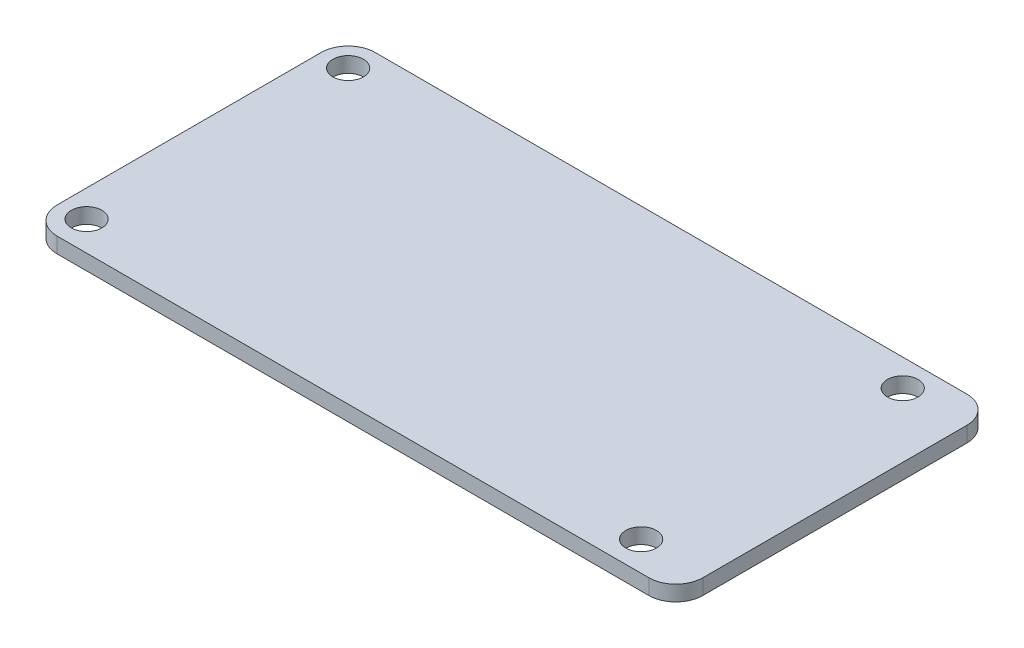
SolidWorks part; units mm, degrees
ref_plane "Front Plane" through (0, 0, 0) normal (0, 0, 1) x (1, 0, 0)
ref_plane "Top Plane" through (0, 0, 0) normal (0, 1, 0) x (1, 0, 0)
ref_plane "Right Plane" through (0, 0, 0) normal (1, 0, 0) x (0, 0, -1)
sketch "Sketch1" plane through (0, 0, 0) normal (0, 1, 0) x (1, 0, 0)
  line L0 (0, 0) -> (0, 27.9326) construction
  line L1 (-33.5, 13.697) -> (-33.5, -13.697)
  line L2 (-30.697, 16.5) -> (30.697, 16.5)
  line L3 (33.5, 13.697) -> (33.5, -13.697)
  line L4 (-30.697, -16.5) -> (30.697, -16.5)
  line L5 (0, 0) -> (-51.5102, 0) construction
  line L6 (-30.697, 13.697) -> (26.843, 13.697) construction
  line L7 (-30.697, 13.697) -> (-30.697, -13.443) construction
  line L8 (-30.697, -13.443) -> (26.843, -13.443) construction
  line L9 (26.843, 13.697) -> (26.843, -13.443) construction
  circle A0 centre (-30.697, 13.697) radius 1.5875
  circle A1 centre (26.843, 13.697) radius 1.5875
  circle A2 centre (26.843, -13.443) radius 1.5875
  circle A3 centre (-30.697, -13.443) radius 1.5875
  arc A4 (-33.5, 13.697) -> (-30.697, 16.5) centre (-30.697, 13.697) cw
  arc A5 (30.697, 16.5) -> (33.5, 13.697) centre (30.697, 13.697) cw
  arc A6 (33.5, -13.697) -> (30.697, -16.5) centre (30.697, -13.697) cw
  arc A7 (-30.697, -16.5) -> (-33.5, -13.697) centre (-30.697, -13.697) cw
  point P4 (-33.5, 0)
  point P6 (0, 0)
  point P29 (0, 16.5)
  dimension "D6" = 3.175
  dimension "D5" = 2.803
  dimension "D1" = 33
  dimension "D2" = 67
  dimension "D3" = 27.14
  dimension "D4" = 57.54
extrude "Boss-Extrude1" add sketch "Sketch1" along normal blind 1.6
